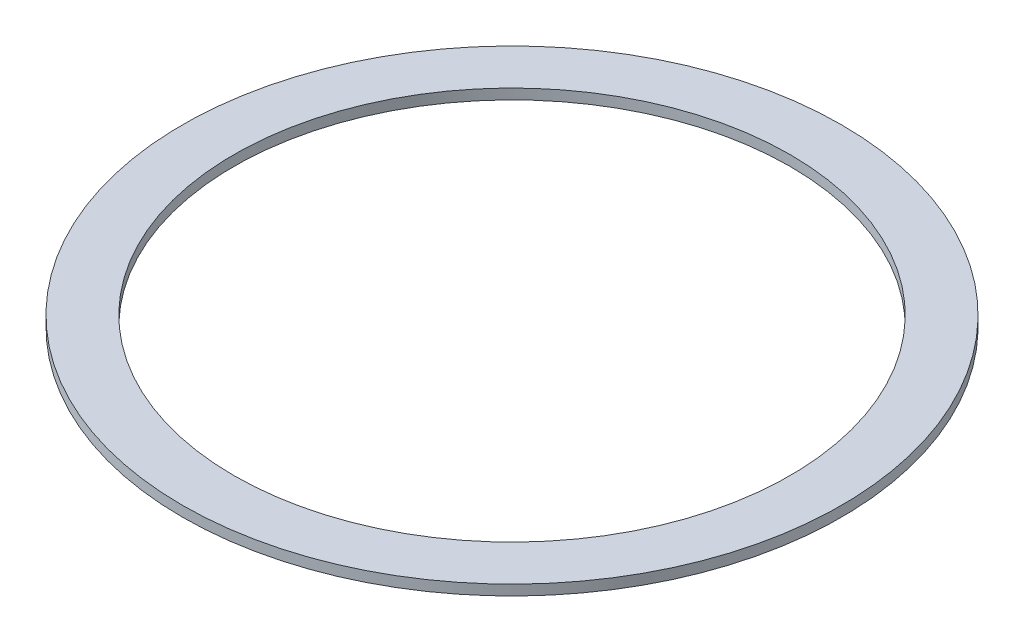
SolidWorks part; units mm, degrees
ref_plane "Plano frontal" through (0, 0, 0) normal (0, 0, 1) x (1, 0, 0)
ref_plane "Plano superior" through (0, 0, 0) normal (0, 1, 0) x (1, 0, 0)
ref_plane "Plano direito" through (0, 0, 0) normal (1, 0, 0) x (0, 0, -1)
sketch "Esboço1" plane through (0, 0, 0) normal (0, 1, 0) x (1, 0, 0)
  circle A0 centre (0, 0) radius 48
  circle A1 centre (0, 0) radius 40.5
  dimension "D1" = 96
  dimension "D2" = 81
extrude "Ressalto-extrusão1" add sketch "Esboço1" along normal blind 1.5
